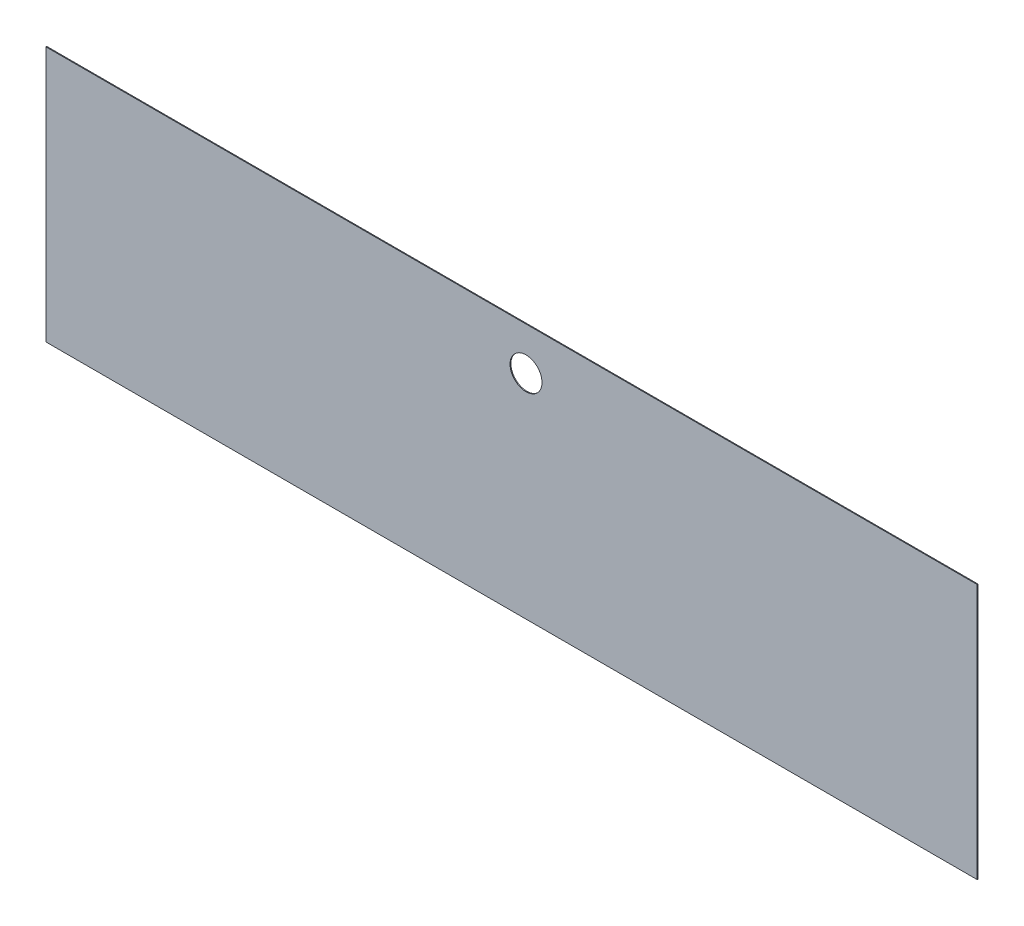
SolidWorks part; units mm, degrees
ref_plane "Alzado" through (0, 0, 0) normal (0, 0, 1) x (1, 0, 0)
ref_plane "Planta" through (0, 0, 0) normal (0, 1, 0) x (1, 0, 0)
ref_plane "Vista lateral" through (0, 0, 0) normal (1, 0, 0) x (0, 0, -1)
sketch "Croquis1" plane through (0, 0, 0) normal (0, 0, 1) x (1, 0, 0)
  line L1 (1093, -300) -> (-1093, -300)
  line L2 (1093, -300) -> (1093, 300)
  line L3 (1093, 300) -> (-1093, 300)
  line L4 (-1093, -300) -> (-1093, 300)
  line L5 (1093, -300) -> (-1093, 300) construction
  line L6 (1093, 300) -> (-1093, -300) construction
  point P0 (0, 0)
  dimension "D1" = 2186
  dimension "D2" = 600
extrude "Extruir1" add sketch "Croquis1" along normal blind 2
sketch "Croquis2" plane through (0, 0, 0) normal (0, 0, -1) x (-1, 0, 0)
  circle A0 centre (-33.9259, 199.774) radius 37.5
  dimension "D1" = 75
extrude "Cortar-Extruir1" cut sketch "Croquis2" against normal blind 10
